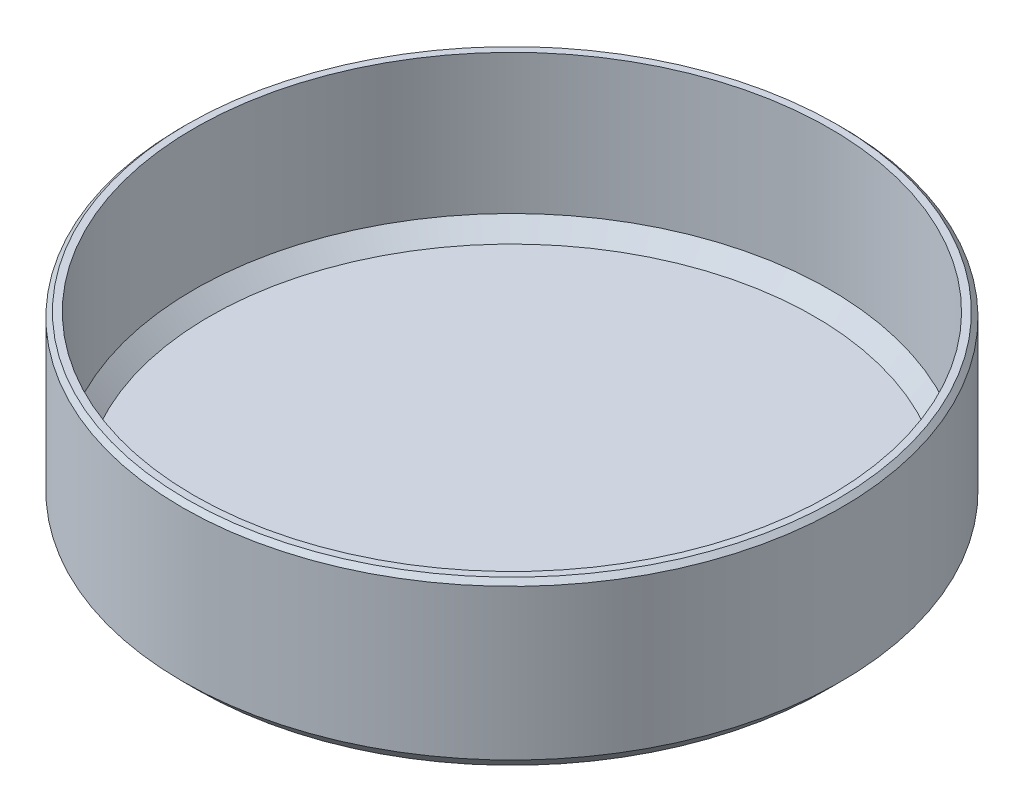
SolidWorks part; units mm, degrees
ref_plane "Front Plane" through (0, 0, 0) normal (0, 0, 1) x (1, 0, 0)
ref_plane "Top Plane" through (0, 0, 0) normal (0, 1, 0) x (1, 0, 0)
ref_plane "Right Plane" through (0, 0, 0) normal (1, 0, 0) x (0, 0, -1)
sketch "Sketch1" plane through (0, 0, 0) normal (0, 1, 0) x (1, 0, 0)
  circle A0 centre (0, 0) radius 42.5
  dimension "D1" = 85
extrude "Boss-Extrude1" add sketch "Sketch1" along normal blind 2
sketch "Sketch2" plane through (0, 2, 0) normal (0, 1, 0) x (1, 0, 0)
  circle A1 centre (0, 0) radius 41
  circle A2 centre (0, 0) radius 42.5
  circle A3 centre (0, 0) radius 42.5
  dimension "D1" = 0
  dimension "D2" = 1.5
extrude "Boss-Extrude2" add sketch "Sketch2" along normal blind 20
chamfer "Chamfer1" distance 2 angle 45 2 edges at (0, 2, 41) (0, 0, 42.5)
chamfer "Chamfer2" distance 0.6 angle 45 1 edges at (0, 22, 42.5)
